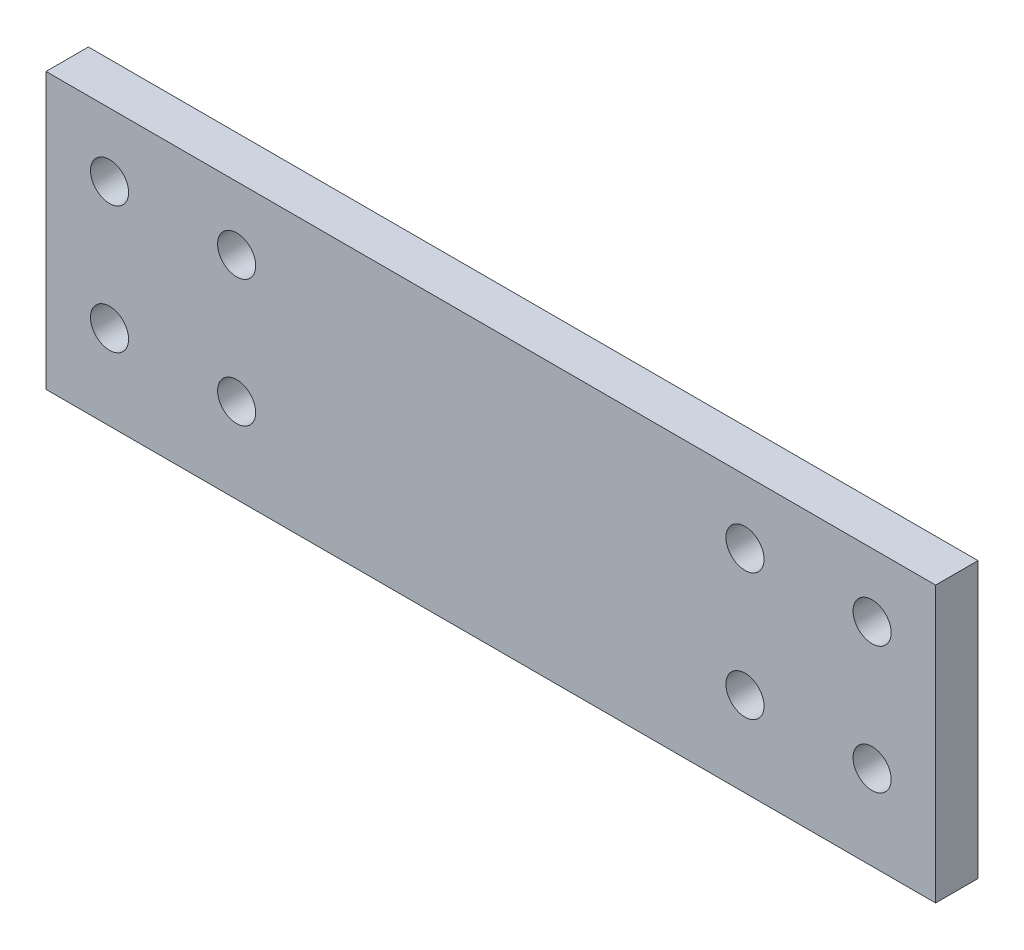
SolidWorks part; units mm, degrees
ref_plane "Front Plane" through (0, 0, 0) normal (0, 0, 1) x (1, 0, 0)
ref_plane "Top Plane" through (0, 0, 0) normal (0, 1, 0) x (1, 0, 0)
ref_plane "Right Plane" through (0, 0, 0) normal (1, 0, 0) x (0, 0, -1)
sketch "Sketch1" plane through (0, 0, 0) normal (0, 0, 1) x (1, 0, 0)
  line L1 (105, -32.5) -> (-105, -32.5)
  line L2 (105, -32.5) -> (105, 32.5)
  line L3 (105, 32.5) -> (-105, 32.5)
  line L4 (-105, -32.5) -> (-105, 32.5)
  line L5 (105, -32.5) -> (-105, 32.5) construction
  line L6 (105, 32.5) -> (-105, -32.5) construction
  point P0 (0, 0)
  dimension "D1" = 210
  dimension "D2" = 65
extrude "Boss-Extrude1" add sketch "Sketch1" along normal blind 10
sketch "Sketch2" plane through (0, 0, 10) normal (0, 0, 1) x (1, 0, 0)
  line L3 (-105, 32.5) -> (-105, -32.5) construction
  line L4 (-105, -32.5) -> (105, -32.5) construction
  line L5 (105, 32.5) -> (-105, 32.5) construction
  circle A6 centre (-90, -12.5) radius 4.5
  circle A7 centre (-90, 17.5) radius 4.5
  circle A8 centre (-60, 17.5) radius 4.5
  circle A9 centre (-60, -12.5) radius 4.5
  circle A14 centre (60, 17.5) radius 4.5
  circle A15 centre (90, 17.5) radius 4.5
  circle A16 centre (60, -12.5) radius 4.5
  circle A17 centre (90, -12.5) radius 4.5
  point P12 (0, 0)
  point P24 (0, 0)
  point P26 (0, 0)
  point P28 (0, 0)
  point P29 (0, 0)
  dimension "D1" = 9
  dimension "D8" = 0
  dimension "D11" = 9
  dimension "D2" = 15
  dimension "D3" = 20
  dimension "D4" = 30
  dimension "D5" = 20
  dimension "D6" = 30
  dimension "D7" = 15
  dimension "D9" = 30
  dimension "D10" = 15
  dimension "D12" = 120
  dimension "D13" = 120
  dimension "D14" = 30
  dimension "D15" = 45
  dimension "D17" = 30
  dimension "D18" = 30
  dimension "D19" = 30
extrude "Cut-Extrude1" cut sketch "Sketch2" against normal up to next
